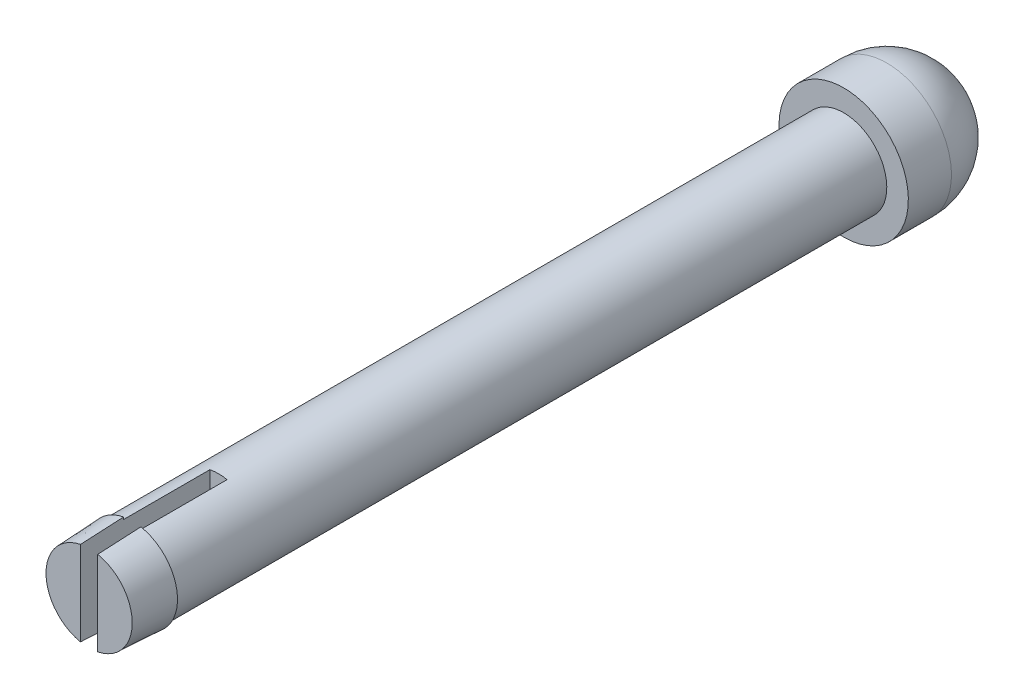
SolidWorks part; units mm, degrees
ref_plane "前视基准面" through (0, 0, 0) normal (0, 0, 1) x (1, 0, 0)
ref_plane "上视基准面" through (0, 0, 0) normal (0, 1, 0) x (1, 0, 0)
ref_plane "右视基准面" through (0, 0, 0) normal (1, 0, 0) x (0, 0, -1)
sketch "草图1" plane through (0, 0, 0) normal (0, 0, 1) x (1, 0, 0)
  circle A0 centre (0, 0) radius 2
extrude "凸台-拉伸1" add sketch "草图1" against normal blind 36
sketch "草图2" plane through (0, 0, 0) normal (1, 0, 0) x (0, 0, -1)
  line L0 (35, 0) -> (40, 0)
  line L1 (37, -3) -> (35, -3)
  line L4 (35, -3) -> (35, 0)
  arc A1 (37, -3) -> (40, 0) centre (37, 0) ccw
revolve "旋转1" add sketch "草图2" angle 360 about L0
sketch "草图3" plane through (0, 0, 0) normal (1, 0, 0) x (0, 0, -1)
  line L0 (0, 2) -> (0, 0)
  line L1 (0, 2) -> (2, 2.1)
  line L2 (2, 2.1) -> (2, 0)
  line L3 (2, 0) -> (0, 0)
revolve "旋转2" add sketch "草图3" angle 360 about L3
sketch "草图4" plane through (0, 0, 0) normal (0, 0, 1) x (1, 0, 0)
  line L2 (-0.4, -2.0616) -> (-0.4, 2.0616)
  line L4 (0.4, -2.0616) -> (0.4, 2.0616)
  arc A0 (0.4, 2.0616) -> (-0.4, 2.0616) centre (0, 0) ccw
  arc A2 (-0.4, -2.0616) -> (0.4, -2.0616) centre (0, 0) ccw
extrude "切除-拉伸1" cut sketch "草图4" against normal blind 6
